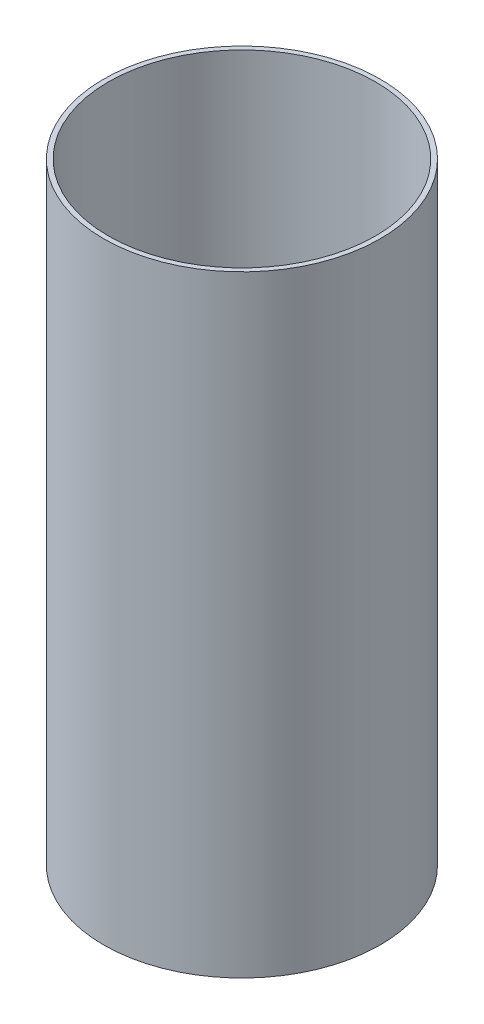
SolidWorks part; units mm, degrees
material "Acrylic (Medium-high impact)"
ref_plane "Front Plane" through (0, 0, 0) normal (0, 0, 1) x (1, 0, 0)
ref_plane "Top Plane" through (0, 0, 0) normal (0, 1, 0) x (1, 0, 0)
ref_plane "Right Plane" through (0, 0, 0) normal (1, 0, 0) x (0, 0, -1)
sketch "Sketch1" plane through (0, 0, 0) normal (0, 1, 0) x (1, 0, 0)
  circle A0 centre (0, 0) radius 92.075
  circle A1 centre (0, 0) radius 88.9
  dimension "D1" = 184.15
  dimension "D2" = 177.8
extrude "Boss-Extrude1" add sketch "Sketch1" along normal mid plane 407.162
ref_plane "Plane1" through (0, 0, 92.075) normal (0, 0, 1) x (1, 0, 0)
sketch "Sketch3" plane through (0, 0, 92.075) normal (0, 0, 1) x (1, 0, 0)
  line L0 (0, -55) -> (0, 55) construction
  line L1 (-92.075, -203.581) -> (92.075, -203.581) construction
  circle A0 centre (0, -197.231) radius 1.4351
  dimension "D1" = 2.8702
  dimension "D2" = 6.35
extrude "Cut-Extrude1" [suppressed] cut sketch "Sketch3" against normal blind 19.304
pattern_circular "CirPattern1" [suppressed] count 12 over 360
mirror "Mirror1" [suppressed] about plane through (0, 0, 0) normal (0, 1, 0)
sketch "Sketch4" [suppressed] plane through (0, 0, 93.6625) normal (0, 0, 1) x (1, 0, 0)
  line L0 (0, -103.0288) -> (0, 103.0288) construction
  circle A0 centre (0, 65.7606) radius 1.4351
  circle A1 centre (0, -65.7606) radius 1.4351
  circle A2 centre (0, 197.231) radius 1.4351 construction
  circle A3 centre (0, -197.231) radius 1.4351 construction
  dimension "D1" = 131.4704
  dimension "D2" = 131.4704
  dimension "D3" = 2.8702
  dimension "D4" = 2.8702
extrude "Cut-Extrude2" [suppressed] cut sketch "Sketch4" against normal blind 43.18
pattern_circular "CirPattern2" [suppressed] count 3 over 360
